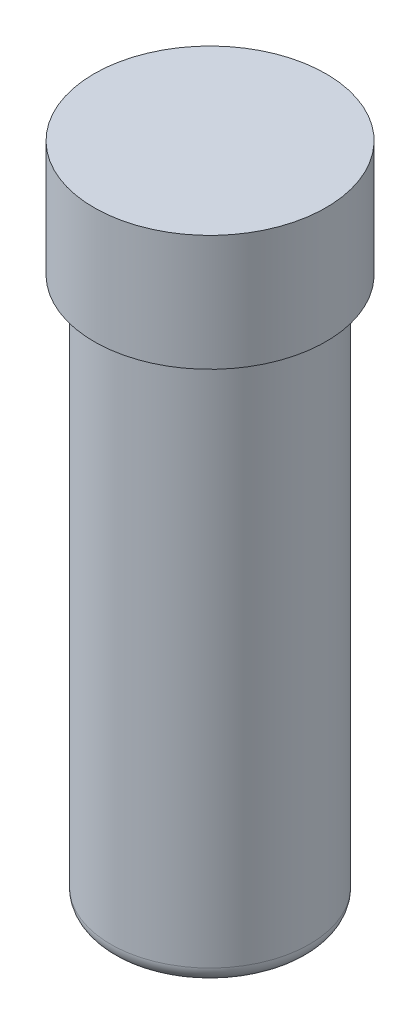
SolidWorks part; units mm, degrees
ref_plane "Front Plane" through (0, 0, 0) normal (0, 0, 1) x (1, 0, 0)
ref_plane "Top Plane" through (0, 0, 0) normal (0, 1, 0) x (1, 0, 0)
ref_plane "Right Plane" through (0, 0, 0) normal (1, 0, 0) x (0, 0, -1)
sketch "Sketch1" plane through (0, 0, 0) normal (0, 0, 1) x (1, 0, 0)
  line L0 (0, 0) -> (6, 0)
  line L1 (6, 0) -> (6, 33)
  line L2 (6, 33) -> (7, 33)
  line L3 (7, 33) -> (7, 40)
  line L4 (7, 40) -> (0, 40)
  line L5 (0, 40) -> (0, 0)
  dimension "D1" = 6
  dimension "D2" = 7
  dimension "D3" = 7
  dimension "D4" = 40
revolve "Revolve1" add sketch "Sketch1" angle 360 about L5
fillet "Fillet1" radius 1 1 edges at (-6, 0, 0)
